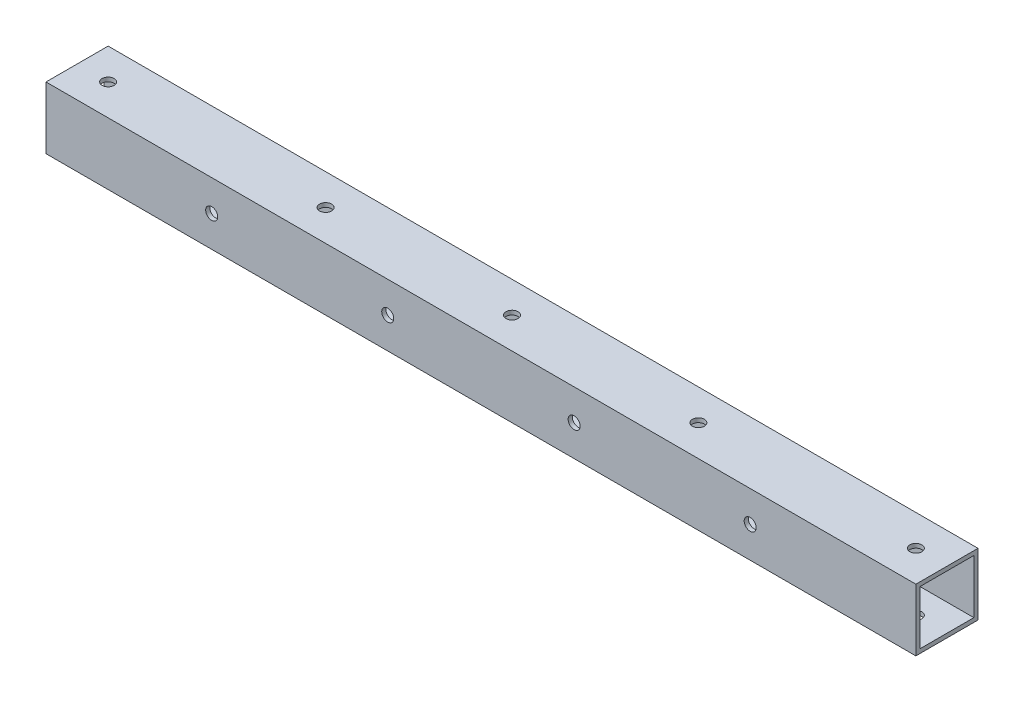
SolidWorks part; units mm, degrees
material "Thornel Mat VMA"
ref_plane "前视基准面" through (0, 0, 0) normal (0, 0, 1) x (1, 0, 0)
ref_plane "上视基准面" through (0, 0, 0) normal (0, 1, 0) x (1, 0, 0)
ref_plane "右视基准面" through (0, 0, 0) normal (1, 0, 0) x (0, 0, -1)
other "Configuration Table"
sketch "草图1" plane through (0, 0, 0) normal (0, 1, 0) x (1, 0, 0)
  line L0 (-105, 0) -> (105, 0)
  dimension "D1" = 210
other "铝管 15X15X1(1)"
ref_plane "基准面1" through (-105, 0, 0) normal (1, 0, 0) x (0, 0, -1)
sketch "草图11" plane through (-105, 0, 0) normal (1, 0, 0) x (0, 0, -1)
  line L1 (-7.5, -7.5) -> (7.5, -7.5)
  line L2 (-7.5, -7.5) -> (-7.5, 7.5)
  line L3 (-7.5, 7.5) -> (7.5, 7.5)
  line L4 (7.5, -7.5) -> (7.5, 7.5)
  line L5 (-7.5, -7.5) -> (7.5, 7.5) construction
  line L6 (-7.5, 7.5) -> (7.5, -7.5) construction
  line L7 (-6.5, -6.5) -> (6.5, -6.5)
  line L8 (-6.5, -6.5) -> (-6.5, 6.5)
  line L9 (-6.5, 6.5) -> (6.5, 6.5)
  line L10 (6.5, -6.5) -> (6.5, 6.5)
  line L11 (-6.5, -6.5) -> (6.5, 6.5) construction
  line L12 (-6.5, 6.5) -> (6.5, -6.5) construction
  point P0 (0, 0)
  point P6 (0, 0)
  point P11 (0, 0)
  dimension "D1" = 15
  dimension "D2" = 15
  dimension "D3" = 13
  dimension "D4" = 13
sketch "草图12" plane through (0, 0, -7.5) normal (0, 0, -1) x (-1, 0, 0)
  line L0 (105, 0) -> (-105, 0) construction
  line L1 (0, 7.5) -> (0, -7.5) construction
  line L2 (-105, 7.5) -> (105, 7.5) construction
  line L3 (-105, -7.5) -> (105, -7.5) construction
  circle A2 centre (22.5, 0) radius 1.45
  circle A3 centre (65, 0) radius 1.45
  circle A4 centre (-65, 0) radius 1.45
  circle A5 centre (-22.5, 0) radius 1.45
  dimension "D1" = 22.5
  dimension "D3" = 2.9
  dimension "D4" = 2.9
  dimension "D5" = 42.5
extrude "切除-拉伸1" cut sketch "草图12" against normal through all
sketch "草图14" plane through (0, 7.5, 0) normal (0, 1, 0) x (1, 0, 0)
  line L0 (-105, 0) -> (105, 0) construction
  line L1 (0, 7.5) -> (0, -7.5) construction
  line L2 (105, 7.5) -> (-105, 7.5) construction
  line L3 (105, -7.5) -> (-105, -7.5) construction
  circle A0 centre (0, 0) radius 1.45
  circle A1 centre (45, 0) radius 1.45
  circle A2 centre (-45, 0) radius 1.45
  dimension "D1" = 2.9
  dimension "D2" = 2.9
  dimension "D3" = 45
extrude "切除-拉伸3" cut sketch "草图14" against normal through all
sketch "草图15" plane through (0, -7.5, 0) normal (0, -1, 0) x (1, 0, 0)
  line L0 (-105, 0) -> (105, 0) construction
  line L1 (-105, 7.5) -> (-105, -7.5) construction
  line L2 (105, 7.5) -> (105, -7.5) construction
  circle A0 centre (-97.5, 0) radius 1.45
  circle A1 centre (97.5, 0) radius 1.45
  dimension "D1" = 2.9
  dimension "D3" = 2.9
  dimension "D4" = 7.5
  dimension "D2" = 7.5
extrude "切除-拉伸4" cut sketch "草图15" against normal through all
